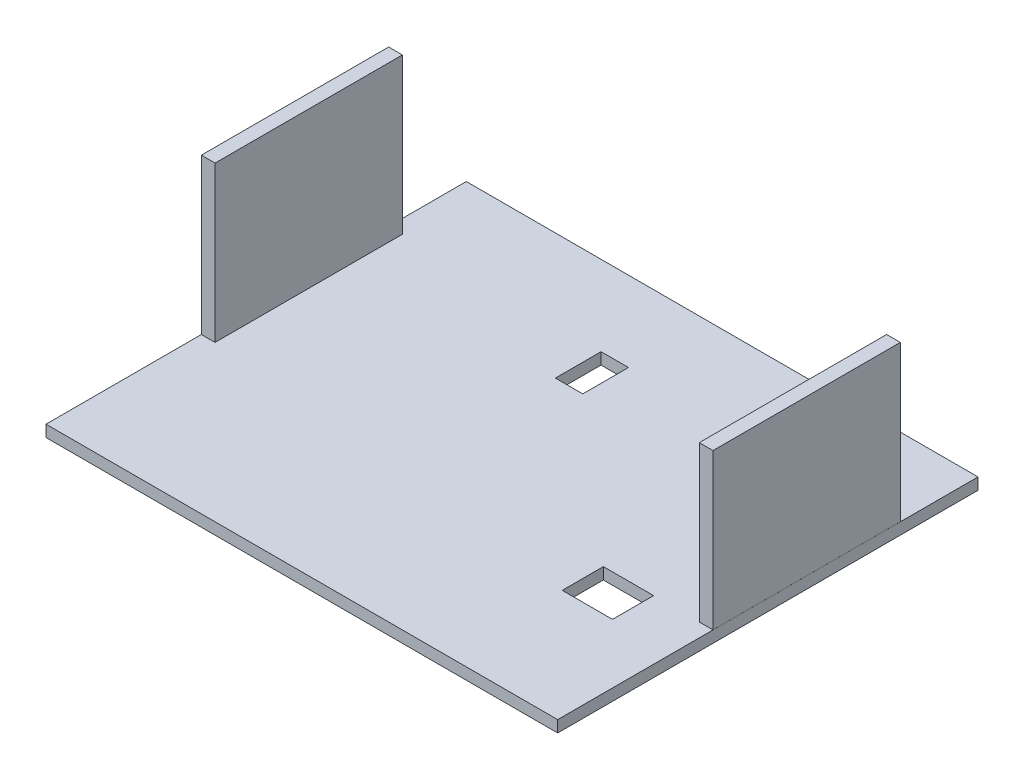
SolidWorks part; units mm, degrees
ref_plane "Front Plane" through (0, 0, 0) normal (0, 0, 1) x (1, 0, 0)
ref_plane "Top Plane" through (0, 0, 0) normal (0, 1, 0) x (1, 0, 0)
ref_plane "Right Plane" through (0, 0, 0) normal (1, 0, 0) x (0, 0, -1)
sketch "Sketch1" plane through (0, 0, 0) normal (0, 1, 0) x (1, 0, 0)
  line L1 (-28, 23) -> (28, 23)
  line L2 (-28, 23) -> (-28, -23)
  line L3 (-28, -23) -> (28, -23)
  line L4 (28, 23) -> (28, -23)
  line L5 (-28, 23) -> (28, -23) construction
  line L6 (-28, -23) -> (28, 23) construction
  point P0 (0, 0)
  dimension "D1" = 56
  dimension "D2" = 46
extrude "Boss-Extrude1" add sketch "Sketch1" along normal blind 1.27
sketch "Sketch2" plane through (0, 1.27, 0) normal (0, 1, 0) x (1, 0, 0)
  line L0 (-28, -23) -> (28, -23) construction
  line L1 (-27.998, 14.5) -> (-26.498, 14.5)
  line L2 (-27.998, 14.5) -> (-27.998, -6)
  line L3 (-27.998, -6) -> (-26.498, -6)
  line L4 (-26.498, 14.5) -> (-26.498, -6)
  line L5 (-27.998, 14.5) -> (-26.498, -6) construction
  line L6 (-27.998, -6) -> (-26.498, 14.5) construction
  line L7 (28, 23) -> (-28, 23) construction
  line L8 (-28, 23) -> (-28, -23) construction
  point P0 (-27.248, 4.25)
  dimension "D1" = 17
  dimension "D2" = 8.5
  dimension "D3" = 0.002
  dimension "D4" = 1.5
extrude "Boss-Extrude2" add sketch "Sketch2" along normal blind 17
mirror "Mirror2" about plane through (0, 0, 0) normal (1, 0, 0) of "Boss-Extrude2"
sketch "Sketch3" plane through (0, 1.27, 0) normal (0, 1, 0) x (1, 0, 0)
  line L0 (-26.498, -6) -> (-26.498, 14.5) construction
  line L1 (-4.498, 14.243) -> (-1.498, 14.243)
  line L2 (-4.498, 14.243) -> (-4.498, 9.243)
  line L3 (-4.498, 9.243) -> (-1.498, 9.243)
  line L4 (-1.498, 14.243) -> (-1.498, 9.243)
  line L5 (-4.498, 14.243) -> (-1.498, 9.243) construction
  line L6 (-4.498, 9.243) -> (-1.498, 14.243) construction
  point P0 (-2.998, 11.743)
  dimension "D1" = 22
  dimension "D2" = 3
  dimension "D3" = 5
extrude "Cut-Extrude1" cut sketch "Sketch3" against normal blind 17
sketch "Sketch4" plane through (0, 1.27, 0) normal (0, 1, 0) x (1, 0, 0)
  line L0 (26.498, -6) -> (26.498, 14.5) construction
  line L1 (15.998, -10.5) -> (21.498, -10.5)
  line L2 (15.998, -10.5) -> (15.998, -6)
  line L3 (15.998, -6) -> (21.498, -6)
  line L4 (21.498, -10.5) -> (21.498, -6)
  line L5 (15.998, -10.5) -> (21.498, -6) construction
  line L6 (15.998, -6) -> (21.498, -10.5) construction
  line L7 (-28, -23) -> (28, -23) construction
  point P0 (18.748, -8.25)
  dimension "D1" = 5
  dimension "D2" = 17
  dimension "D3" = 4.5
  dimension "D4" = 5.5
extrude "Cut-Extrude2" cut sketch "Sketch4" against normal blind 17
